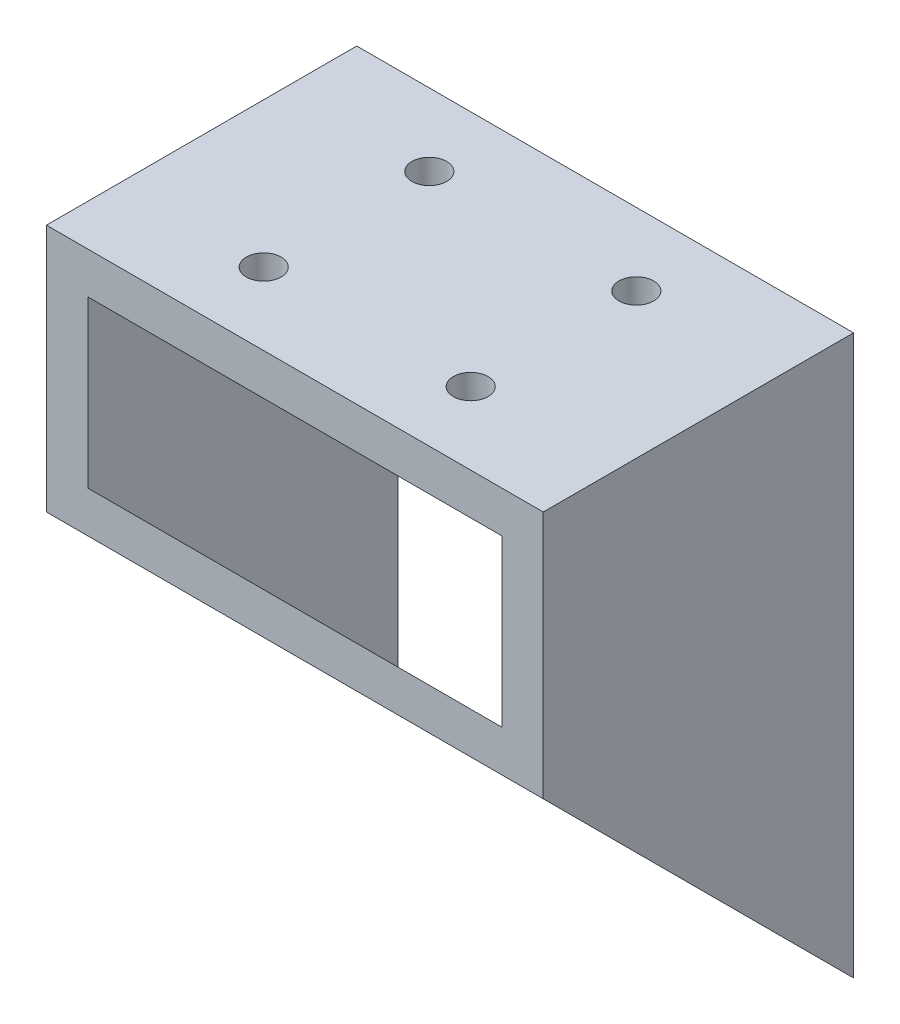
SolidWorks part; units mm, degrees
ref_plane "前视基准面" through (0, 0, 0) normal (0, 0, 1) x (1, 0, 0)
ref_plane "上视基准面" through (0, 0, 0) normal (0, 1, 0) x (1, 0, 0)
ref_plane "右视基准面" through (0, 0, 0) normal (1, 0, 0) x (0, 0, -1)
sketch "草图2" plane through (0, 0, 0) normal (1, 0, 0) x (0, 0, -1)
  line L0 (0, 30) -> (0, 0)
  line L1 (0, 0) -> (37.4767, -37.4767)
  line L2 (37.4767, -37.4767) -> (37.4767, 30)
  line L3 (0, 30) -> (37.4767, 30)
  dimension "D1" = 45
  dimension "D2" = 53
  dimension "D3" = 30
extrude "凸台-拉伸1" add sketch "草图2" along normal blind 5
sketch "草图3" plane through (0, 0, 0) normal (0, -0.7071, 0.7071) x (1, 0, 0)
  line L0 (30, 0) -> (30, -53) construction
  line L1 (5, -53) -> (55, -53)
  line L2 (5, -53) -> (5, 0)
  line L3 (5, 0) -> (55, 0)
  line L4 (55, -53) -> (55, 0)
  line L5 (5, -53) -> (55, 0) construction
  line L6 (5, 0) -> (55, -53) construction
  line L7 (45, -11) -> (45, -41) construction
  line L8 (47.1, -11) -> (47.1, -41)
  line L9 (42.9, -11) -> (42.9, -41)
  line L10 (15, -11) -> (15, -41) construction
  line L11 (12.9, -11) -> (12.9, -41)
  line L12 (17.1, -11) -> (17.1, -41)
  arc A0 (47.1, -11) -> (42.9, -11) centre (45, -11) ccw
  arc A1 (42.9, -41) -> (47.1, -41) centre (45, -41) ccw
  arc A2 (12.9, -11) -> (17.1, -11) centre (15, -11) cw
  arc A3 (17.1, -41) -> (12.9, -41) centre (15, -41) cw
  point P4 (30, -26.5)
  point P10 (45, -26)
  point P17 (15, -26)
  dimension "D2" = 2.1
  dimension "D1" = 50
  dimension "D3" = 15
  dimension "D4" = 11
  dimension "D5" = 30
sketch "草图4" plane through (5, 0, 0) normal (1, 0, 0) x (0, 0, -1)
  line L0 (0, 0) -> (0, 5)
  line L1 (0, 30) -> (0, 0) construction
  line L2 (0, 5) -> (37.4767, -32.4767)
  line L3 (37.4767, -37.4767) -> (37.4767, 30) construction
  line L4 (37.4767, -32.4767) -> (37.4767, -37.4767)
  line L5 (0, 0) -> (37.4767, -37.4767)
  dimension "D1" = 5
extrude "凸台-拉伸3" add sketch "草图4" along normal blind 50
extrude "切除-拉伸2" cut sketch "草图3" against normal blind 50 contours A3 L12 A2 L11 | L9 A1 L8 A0
sketch "草图5" plane through (55, 0, 0) normal (1, 0, 0) x (0, 0, -1)
  line L0 (0, 30) -> (0, 0)
  line L1 (0, 0) -> (37.4767, -37.4767)
  line L2 (37.4767, -37.4767) -> (37.4767, 30)
  line L3 (37.4767, 30) -> (0, 30)
extrude "凸台-拉伸4" add sketch "草图5" along normal blind 5
sketch "草图6" plane through (0, 30, 0) normal (0, 1, 0) x (1, 0, 0)
  line L1 (0, 0) -> (60, 0)
  line L2 (0, 0) -> (0, 37.4767)
  line L3 (0, 37.4767) -> (60, 37.4767)
  line L4 (60, 0) -> (60, 37.4767)
  line L5 (0, 0) -> (60, 37.4767) construction
  line L6 (0, 37.4767) -> (60, 0) construction
  point P4 (30, 18.7383)
extrude "凸台-拉伸5" add sketch "草图6" against normal blind 5
sketch "草图7" plane through (0, 30, 0) normal (0, 1, 0) x (1, 0, 0)
  line L0 (30, 37.4767) -> (30, 0) construction
  line L1 (60, 37.4767) -> (0, 37.4767) construction
  line L2 (60, 0) -> (0, 0) construction
  line L3 (0, 18.7383) -> (60, 18.7383) construction
  line L4 (0, 37.4767) -> (0, 0) construction
  line L5 (60, 37.4767) -> (60, 0) construction
  circle A0 centre (42.5, 28.7383) radius 2.1
  circle A1 centre (17.5, 28.7383) radius 2.1
  circle A2 centre (42.5, 8.7383) radius 2.1
  circle A3 centre (17.5, 8.7383) radius 2.1
  dimension "D1" = 4.2
  dimension "D2" = 25
  dimension "D3" = 20
extrude "切除-拉伸3" cut sketch "草图7" against normal blind 5
